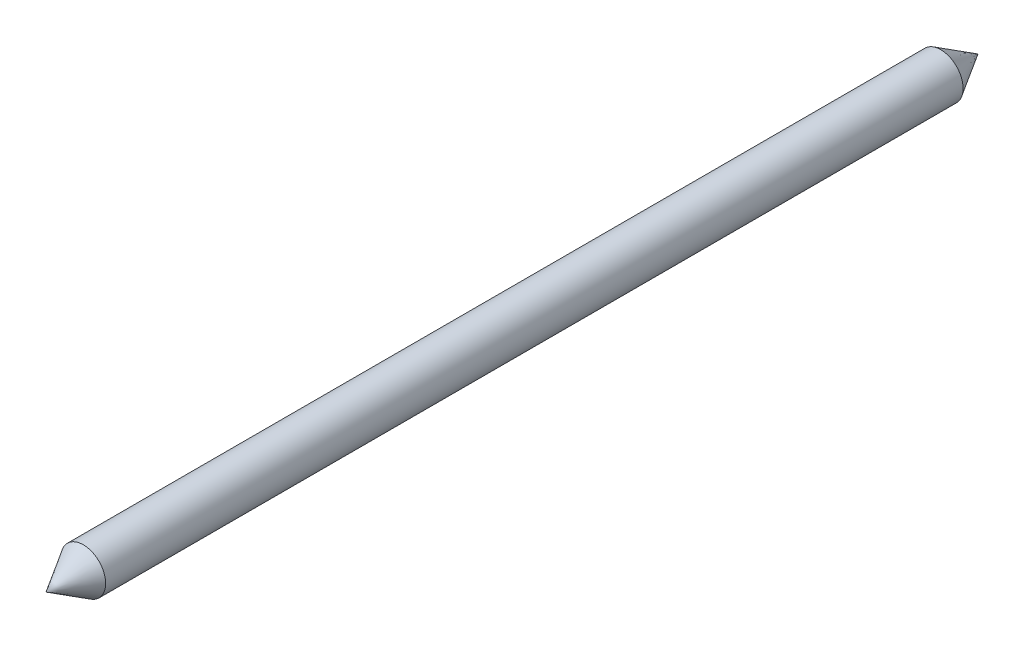
SolidWorks part; units mm, degrees
ref_plane "Front Plane" through (0, 0, 0) normal (0, 0, 1) x (1, 0, 0)
ref_plane "Top Plane" through (0, 0, 0) normal (0, 1, 0) x (1, 0, 0)
ref_plane "Right Plane" through (0, 0, 0) normal (1, 0, 0) x (0, 0, -1)
sketch "Sketch1" plane through (0, 0, 0) normal (0, 1, 0) x (1, 0, 0)
  line L0 (7.62, 146.05) -> (7.62, -146.05)
  line L1 (7.62, 146.05) -> (0, 158.75)
  line L2 (0, 158.75) -> (0, -158.75)
  line L3 (0, -158.75) -> (7.62, -146.05)
  point P5 (0, 0)
  dimension "D1" = 317.5
  dimension "D2" = 12.7
  dimension "D3" = 12.7
  dimension "D4" = 7.62
revolve "Revolve1" add sketch "Sketch1" angle 360 about L2
